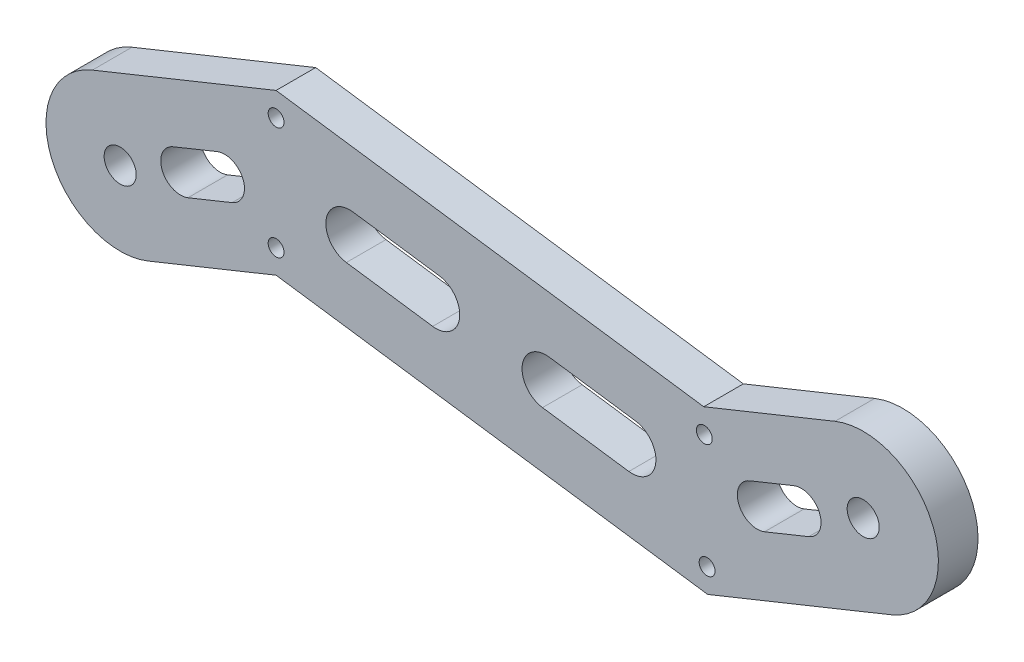
SolidWorks part; units mm, degrees
ref_plane "Front Plane" through (0, 0, 0) normal (0, 0, 1) x (1, 0, 0)
ref_plane "Top Plane" through (0, 0, 0) normal (0, 1, 0) x (1, 0, 0)
ref_plane "Right Plane" through (0, 0, 0) normal (1, 0, 0) x (0, 0, -1)
sketch "Sketch2" plane through (0, 0, 0) normal (0, 0, 1) x (1, 0, 0)
  line L0 (-52.5256, 39.0736) -> (55.4083, 23.9045)
  line L1 (-52.5256, -1.3195) -> (56.4039, -16.6285)
  line L2 (55.4083, 23.9045) -> (88.5451, 37.2926)
  line L3 (56.4039, -16.6285) -> (102.7631, 2.1018)
  line L4 (-52.5256, 39.0736) -> (-98.8848, 20.3433)
  line L5 (-52.5256, -1.3195) -> (-84.8551, -14.3815)
  line L6 (-52.5256, 39.0736) -> (-52.5256, -1.3195) construction
  line L7 (55.4083, 23.9045) -> (56.4039, -16.6285) construction
  line L8 (-91.8699, 2.9809) -> (-52.5256, 18.8771) construction
  line L9 (-52.5256, 18.8771) -> (55.9061, 3.638) construction
  line L10 (55.9061, 3.638) -> (95.6541, 19.6972) construction
  line L11 (-33.9594, 16.2678) -> (-12.1735, 13.2059) construction
  line L12 (-122.2976, 38.9357) -> (124.4009, 38.9357) construction
  line L13 (-122.2976, 38.9357) -> (-122.2976, -26.3788) construction
  line L14 (-122.2976, -26.3788) -> (124.4009, -26.3788) construction
  line L15 (124.4009, 38.9357) -> (124.4009, -26.3788) construction
  line L16 (-33.1244, 22.2094) -> (-11.3385, 19.1476)
  line L17 (-34.7944, 10.3261) -> (-13.0085, 7.2643)
  line L18 (-76.6324, 9.1373) -> (-65.5062, 13.6326) construction
  line L19 (-78.5054, 13.7732) -> (-67.3792, 18.2685)
  line L20 (-74.7593, 4.5014) -> (-63.6331, 8.9967)
  line L21 (68.8867, 8.8825) -> (80.0129, 13.3778) construction
  line L22 (67.0136, 13.5184) -> (78.1399, 18.0137)
  line L23 (70.7597, 4.2466) -> (81.8859, 8.7418)
  line L24 (15.554, 9.3091) -> (37.3399, 6.2473) construction
  line L25 (16.389, 15.2507) -> (38.1749, 12.1889)
  line L26 (14.719, 3.3675) -> (36.5049, 0.3057)
  line L27 (1.6903, 11.2575) -> (2.7609, 18.8756) construction
  arc A0 (88.5451, 37.2926) -> (102.7631, 2.1018) centre (95.6541, 19.6972) cw
  arc A1 (-98.8848, 20.3433) -> (-84.8551, -14.3815) centre (-91.8699, 2.9809) ccw
  circle A2 centre (-91.8699, 2.9809) radius 4.05
  circle A3 centre (95.6541, 19.6972) radius 4.05
  circle A4 centre (-52.5256, 33.0736) radius 2
  circle A5 centre (55.5557, 17.9045) radius 2
  arc A6 (-78.5054, 13.7732) -> (-74.7593, 4.5014) centre (-76.6324, 9.1373) ccw
  arc A7 (-63.6331, 8.9967) -> (-67.3792, 18.2685) centre (-65.5062, 13.6326) ccw
  arc A8 (67.0136, 13.5184) -> (70.7597, 4.2466) centre (68.8867, 8.8825) ccw
  arc A9 (81.8859, 8.7418) -> (78.1399, 18.0137) centre (80.0129, 13.3778) ccw
  circle A10 centre (-52.5256, 4.6805) radius 2
  circle A11 centre (56.2565, -10.6285) radius 2
  arc A12 (-33.1244, 22.2094) -> (-34.7944, 10.3261) centre (-33.9594, 16.2678) ccw
  arc A13 (-13.0085, 7.2643) -> (-11.3385, 19.1476) centre (-12.1735, 13.2059) ccw
  arc A14 (16.389, 15.2507) -> (14.719, 3.3675) centre (15.554, 9.3091) ccw
  arc A15 (36.5049, 0.3057) -> (38.1749, 12.1889) centre (37.3399, 6.2473) ccw
  point P27 (-71.0693, 11.3849)
  point P34 (74.4498, 11.1301)
  point P42 (-23.0665, 14.7368)
  point P47 (26.447, 7.7782)
  dimension "D15" = 8.1
  dimension "D16" = 8.1
  dimension "D7" = 4
  dimension "D17" = 4
  dimension "D22" = 4
  dimension "D23" = 4
  dimension "D1" = 150
  dimension "D2" = 110
  dimension "D3" = 50
  dimension "D4" = 8
  dimension "D5" = 150
  dimension "D6" = 12
  dimension "D8" = 20
  dimension "D9" = 12
  dimension "D10" = 20
  dimension "D11" = 50
  dimension "D12" = 20
  dimension "D13" = 10
  dimension "D14" = 10
  dimension "D18" = 6
  dimension "D19" = 6
  dimension "D20" = 6
  dimension "D21" = 6
  dimension "D24" = 25
  dimension "D25" = 22
  dimension "D26" = 25
  dimension "D27" = 22
  dimension "D28" = 12
  dimension "D29" = 12
extrude "Boss-Extrude1" add sketch "Sketch2" along normal blind 10
